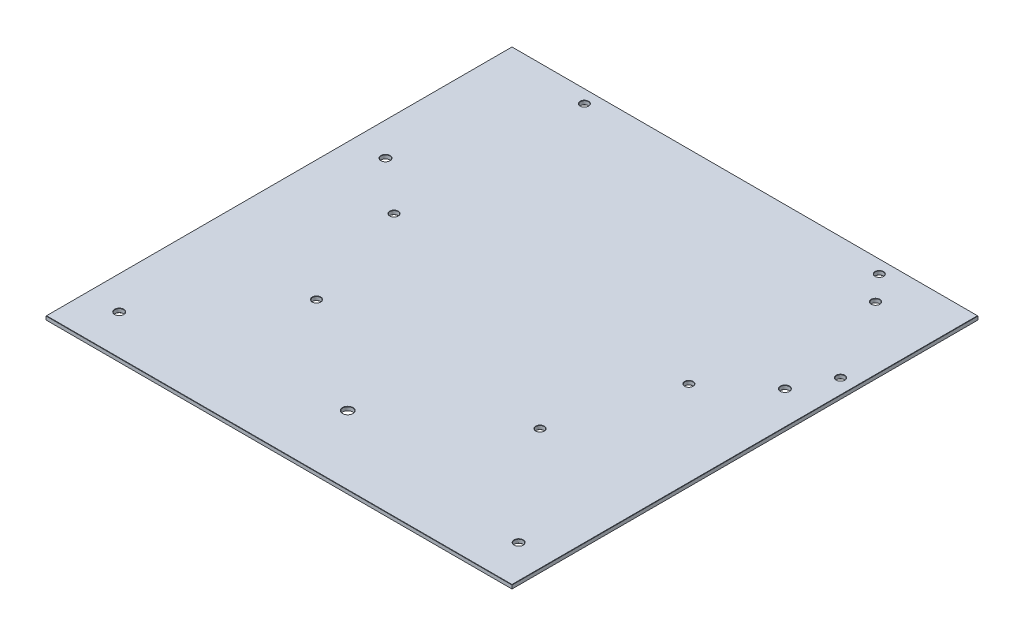
SolidWorks part; units mm, degrees
ref_plane "Front Plane" through (0, 0, 0) normal (0, 0, 1) x (1, 0, 0)
ref_plane "Top Plane" through (0, 0, 0) normal (0, 1, 0) x (1, 0, 0)
ref_plane "Right Plane" through (0, 0, 0) normal (1, 0, 0) x (0, 0, -1)
sketch "Sketch1" plane through (0, 0, 0) normal (0, 1, 0) x (1, 0, 0)
  line L1 (-175, 175) -> (175, 175)
  line L2 (-175, 175) -> (-175, -175)
  line L3 (-175, -175) -> (175, -175)
  line L4 (175, 175) -> (175, -175)
  line L5 (-175, 175) -> (175, -175) construction
  line L6 (-175, -175) -> (175, 175) construction
  point P0 (0, 0)
  dimension "D1" = 350
extrude "Boss-Extrude1" add sketch "Sketch1" along normal blind 3
sketch "Sketch6" plane through (0, 3, 0) normal (0, 1, 0) x (1, 0, 0)
  line L0 (-175, 55) -> (175, 55) construction
  line L1 (-175, 175) -> (-175, -175) construction
  line L2 (175, -175) -> (175, 175) construction
  line L3 (-150, -145) -> (-175, -145) construction
  line L4 (150, -145) -> (175, -145) construction
  line B0 (-150, -145) -> (150, -145) construction
  line B1 (150, -145) -> (150, 55) construction
  line B2 (150, 55) -> (-150, 55) construction
  line B3 (-150, 55) -> (-150, -145) construction
  line B4 (-150, -145) -> (150, 55) construction
  circle B5 centre (-150, -145) radius 3
  circle B6 centre (150, 55) radius 3
  circle B7 centre (150, -145) radius 3
  circle B8 centre (-150, 55) radius 3
sketch_block_instance "Block2-1"
sketch_block "Block2"
sketch "Sketch2" plane through (0, 3, 0) normal (0, 1, 0) x (1, 0, 0)
  line L0 (-175, 175) -> (-175, 55) construction
  line L1 (-175, 175) -> (-175, -175) construction
  line L2 (-175, 55) -> (175, 55) construction
  line L3 (175, -175) -> (175, 175) construction
  line L4 (-155, -175) -> (-155, -155) construction
  line L5 (-175, -175) -> (175, -175) construction
  line L6 (-155, -155) -> (155, -155) construction
  line L7 (155, -155) -> (155, -175) construction
  line L8 (-155, -155) -> (-155, -151.75) construction
  line L9 (155, -155) -> (155, -151.75) construction
  line L10 (155, -151.75) -> (-155, -151.75) construction
  line L11 (-151.75, 55) -> (-151.75, -151.75) construction
  line L12 (-151.75, -151.75) -> (151.75, 55) construction
  line L13 (151.75, 55) -> (151.75, -151.75) construction
  line L14 (151.75, -151.75) -> (-151.75, 55) construction
  line L15 (0, -48.375) -> (0, -123.375) construction
  circle A1 centre (-151.75, -151.75) radius 3.25 construction
  circle A2 centre (151.75, -151.75) radius 3.25 construction
  circle A3 centre (151.75, 55) radius 3.25 construction
  circle A4 centre (-151.75, 55) radius 3.25 construction
  circle A6 centre (0, -123.375) radius 3.75
  circle A7 centre (-150, 55) radius 3 construction
  circle A8 centre (150, 55) radius 3 construction
  circle A9 centre (150, -145) radius 3 construction
  circle A10 centre (-150, -145) radius 3 construction
  circle A11 centre (-150, 55) radius 3 construction
  circle A12 centre (150, 55) radius 3 construction
  circle A13 centre (150, -145) radius 3 construction
  circle A14 centre (-150, -145) radius 3 construction
  circle A15 centre (-150, -145) radius 3.25
  circle A16 centre (-150, 55) radius 3.25
  circle A17 centre (150, 55) radius 3.25
  circle A18 centre (150, -145) radius 3.25
  point P8 (-155, 55)
  point P9 (155, 55)
  dimension "D6" = 6.5
  dimension "D7" = 7.5
  dimension "D8" = 6.5
  dimension "D1" = 120
  dimension "D2" = 20
  dimension "D3" = 20
  dimension "D4" = 20
  dimension "D5" = 75
extrude "Cut-Extrude1" cut sketch "Sketch2" against normal up to surface (3 mm away) up to face at (0, 0, 0)
sketch "Sketch3" plane through (0, 3, 0) normal (0, 1, 0) x (1, 0, 0)
  circle A0 centre (-83.95, -62.9016) radius 3.05 construction
  circle A1 centre (83.95, -62.9016) radius 3.05 construction
  circle A2 centre (-83.95, -62.9016) radius 3.05
  circle A3 centre (83.95, -62.9016) radius 3.05
extrude "Cut-Extrude2" cut sketch "Sketch3" against normal up to surface (3 mm away) up to face at (150, 0, 148.25)
sketch "Sketch4" plane through (0, 3, 0) normal (0, 1, 0) x (1, 0, 0)
  circle A0 centre (-110.733, 165.1108) radius 3 construction
  circle A1 centre (-110.733, 165.1108) radius 3
  circle A2 centre (-110.75, 22.1108) radius 3 construction
  circle A3 centre (110.75, 22.0845) radius 3 construction
  circle A4 centre (110.767, 165.0845) radius 3 construction
  circle A5 centre (-110.75, 22.1108) radius 3
  circle A6 centre (110.75, 22.0845) radius 3
  circle A7 centre (110.767, 165.0845) radius 3
extrude "Cut-Extrude3" cut sketch "Sketch4" against normal up to surface (3 mm away) up to face at (-83.95, 0, 65.9516)
sketch "Sketch5" plane through (0, 3, 0) normal (0, 1, 0) x (1, 0, 0)
  circle A4 centre (163.7076, 83.0307) radius 3.05 construction
  circle A5 centre (127.4584, 145.5807) radius 3.05 construction
  circle A6 centre (163.7076, 83.0307) radius 3.05
  circle A7 centre (127.4584, 145.5807) radius 3.05
extrude "Cut-Extrude4" cut sketch "Sketch5" against normal up to surface (3 mm away) up to face at (110.767, 0, -162.0845)
chamfer "Chamfer1" distance 0.2 angle 45 34 edges at (0, 0, -175) (-175, 0, 0) (0, 0, 175) (175, 0, 0) (0, 0, 127.125) (83.95, 0, 65.9516) (-83.95, 0, 65.9516) (-110.733, 0, -162.1108) (-110.75, 0, -19.1108) (110.75, 0, -19.0845) (110.767, 0, -162.0845) (127.4584, 0, -142.5307) (163.7076, 0, -79.9807) (0, 3, 175) (-175, 3, 0) (0, 3, -175) (175, 3, 0) (0, 3, 127.125) (83.95, 3, 65.9516) (-83.95, 3, 65.9516) (-110.733, 3, -162.1108) (-110.75, 3, -19.1108) (110.75, 3, -19.0845) (110.767, 3, -162.0845) (127.4584, 3, -142.5307) (163.7076, 3, -79.9807) (-150, 0, 148.25) (-150, 0, -51.75) (150, 0, -51.75) (150, 0, 148.25) (-150, 3, 148.25) (-150, 3, -51.75) (150, 3, -51.75) (150, 3, 148.25)
sketch "Sketch7" plane through (0, 3, 0) normal (0, 1, 0) x (1, 0, 0)
  circle A0 centre (-150, -145) radius 3.25 construction
  circle A1 centre (-150, -145) radius 3.25
sketch "Sketch8" plane through (-175, 0, 0) normal (-1, 0, 0) x (0, 0, 1)
  line L0 (145, 3) -> (145, -18.5807)
  line L1 (148.25, 3) -> (141.75, 3) construction
